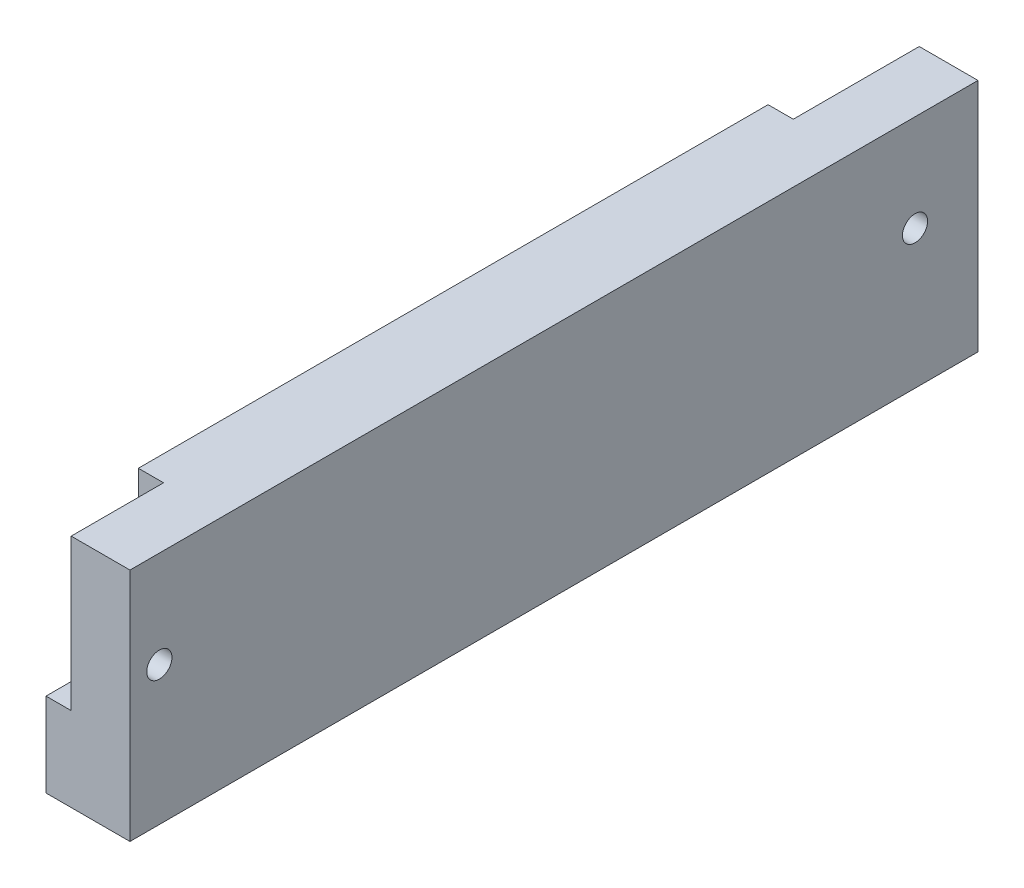
SolidWorks part; units mm, degrees
ref_plane "前视基准面" through (0, 0, 0) normal (0, 0, 1) x (1, 0, 0)
ref_plane "上视基准面" through (0, 0, 0) normal (0, 1, 0) x (1, 0, 0)
ref_plane "右视基准面" through (0, 0, 0) normal (1, 0, 0) x (0, 0, -1)
sketch "草图1" plane through (0, 0, 0) normal (0, 0, 1) x (1, 0, 0)
  line L1 (-5, 14) -> (5, 14)
  line L2 (-5, 14) -> (-5, -14)
  line L3 (-5, -14) -> (5, -14)
  line L4 (5, 14) -> (5, -14)
  line L5 (-5, 14) -> (5, -14) construction
  line L6 (-5, -14) -> (5, 14) construction
  point P0 (0, 0)
  dimension "D1" = 28
  dimension "D2" = 10
extrude "凸台-拉伸1" add sketch "草图1" along normal blind 105
sketch "草图2" plane through (0, -14, 0) normal (0, -1, 0) x (1, 0, 0)
  line L0 (0, 105) -> (0, 0) construction
  line L1 (-5, 105) -> (5, 105) construction
  line L2 (-5, 52.5) -> (5, 52.5) construction
  line L3 (-5, 105) -> (-5, 0) construction
  line L4 (5, 105) -> (5, 0) construction
  circle A0 centre (0, 97.5) radius 1.5
  circle A1 centre (0, 7.5) radius 1.5
  dimension "D1" = 3
  dimension "D3" = 3
  dimension "D2" = 45
  dimension "D4" = 45
extrude "切除-拉伸1" cut sketch "草图2" against normal blind 10
sketch "草图3" plane through (-5, 0, 0) normal (-1, 0, 0) x (0, 0, 1)
  line L0 (0, 2.5) -> (105, 2.5) construction
  line L1 (0, 14) -> (0, -14) construction
  line L2 (105, 14) -> (105, -14) construction
  line L3 (105, -14) -> (0, -14) construction
  line L4 (52.5, 14) -> (52.5, -14) construction
  line L5 (105, 14) -> (0, 14) construction
  circle A0 centre (7.5, 2.5) radius 1.5
  circle A1 centre (97.5, 2.5) radius 1.5
  dimension "D4" = 3
  dimension "D5" = 3
  dimension "D1" = 16.5
  dimension "D2" = 45
  dimension "D3" = 45
extrude "切除-拉伸2" cut sketch "草图3" against normal through all
sketch "草图4" plane through (-5, 0, 0) normal (-1, 0, 0) x (0, 0, 1)
  line L1 (0, 14) -> (15, 14)
  line L2 (0, 14) -> (0, -4)
  line L3 (0, -4) -> (15, -4)
  line L4 (15, 14) -> (15, -4)
  line L5 (105, 14) -> (90, 14)
  line L6 (105, 14) -> (105, -4)
  line L7 (105, -4) -> (90, -4)
  line L8 (90, 14) -> (90, -4)
  dimension "D1" = 18
  dimension "D2" = 18
  dimension "D3" = 15
  dimension "D4" = 15
extrude "切除-拉伸3" cut sketch "草图4" against normal blind 3
sketch "草图5" plane through (0, 0, 105) normal (0, 0, 1) x (1, 0, 0)
  line L1 (-8.5906, 16.5671) -> (10.7068, 16.5671)
  line L2 (-8.5906, 16.5671) -> (-8.5906, -17.3648)
  line L3 (-8.5906, -17.3648) -> (10.7068, -17.3648)
  line L4 (10.7068, 16.5671) -> (10.7068, -17.3648)
extrude "切除-拉伸6" cut sketch "草图5" against normal blind 4
